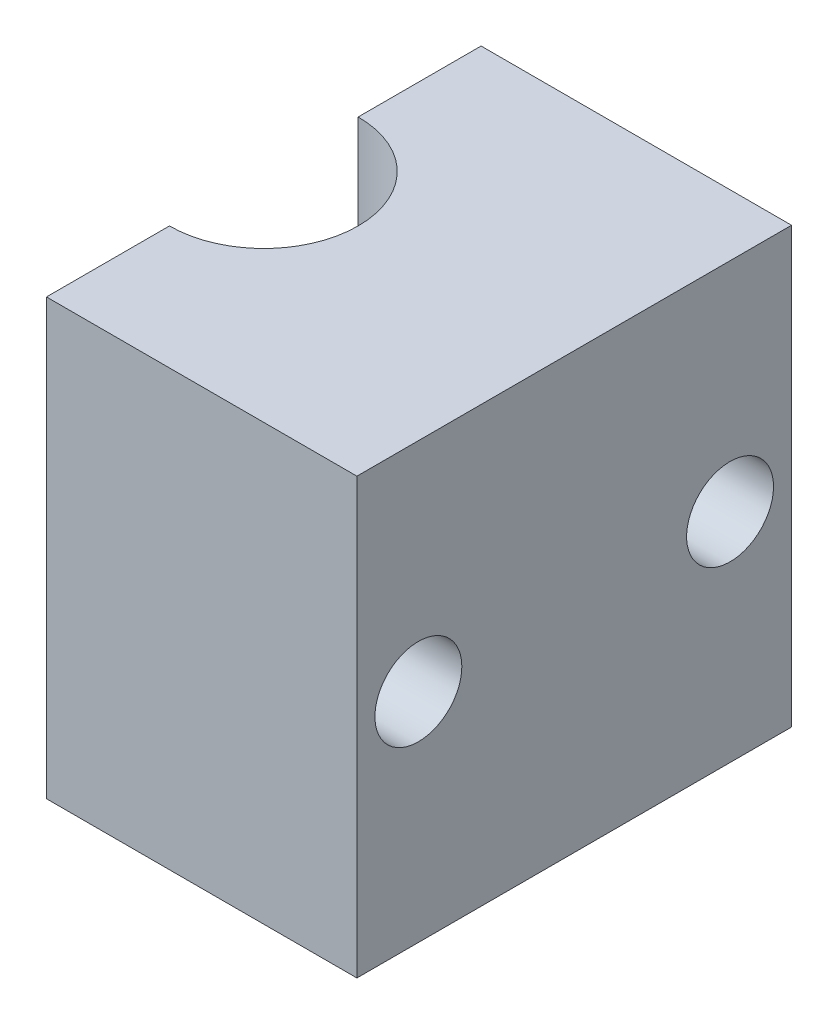
SolidWorks part; units mm, degrees
ref_plane "Front Plane" through (0, 0, 0) normal (0, 0, 1) x (1, 0, 0)
ref_plane "Top Plane" through (0, 0, 0) normal (0, 1, 0) x (1, 0, 0)
ref_plane "Right Plane" through (0, 0, 0) normal (1, 0, 0) x (0, 0, -1)
sketch "Sketch1" plane through (0, 0, 0) normal (0, 1, 0) x (1, 0, 0)
  line L0 (-32.48, -7.6) -> (-32.48, -17.5)
  line L1 (-32.48, 17.5) -> (-7.48, 17.5)
  line L2 (-32.48, 17.5) -> (-32.48, 7.6)
  line L3 (-32.48, -17.5) -> (-7.48, -17.5)
  line L4 (-7.48, 17.5) -> (-7.48, -17.5)
  line L5 (-32.48, 17.5) -> (-7.48, -17.5) construction
  line L6 (-32.48, -17.5) -> (-7.48, 17.5) construction
  arc A0 (-32.48, -7.6) -> (-32.48, 7.6) centre (-32.48, 0) ccw
  point P0 (-19.98, 0)
  dimension "D1" = 35
  dimension "D2" = 25
extrude "Boss-Extrude1" add sketch "Sketch1" along normal blind 35
sketch "Sketch3" plane through (-32.48, 0, 0) normal (-1, 0, 0) x (0, 0, 1)
  circle A0 centre (0, 17.5) radius 6.3
  dimension "D1" = 12.6
extrude "Cut-Extrude1" cut sketch "Sketch3" against normal blind 20
sketch "Sketch4" plane through (-32.48, 0, 0) normal (-1, 0, 0) x (0, 0, 1)
  circle A0 centre (12.55, 17.5) radius 1.5
  circle A2 centre (-12.55, 17.5) radius 1.5
extrude "Cut-Extrude2" cut sketch "Sketch4" against normal through all
sketch "Sketch5" plane through (-7.48, 0, 0) normal (1, 0, 0) x (0, 0, -1)
  circle A0 centre (-12.55, 17.5) radius 3.5
  circle A1 centre (12.55, 17.5) radius 3.5
  dimension "D1" = 7
  dimension "D2" = 7
extrude "Cut-Extrude3" cut sketch "Sketch5" against normal blind 5
